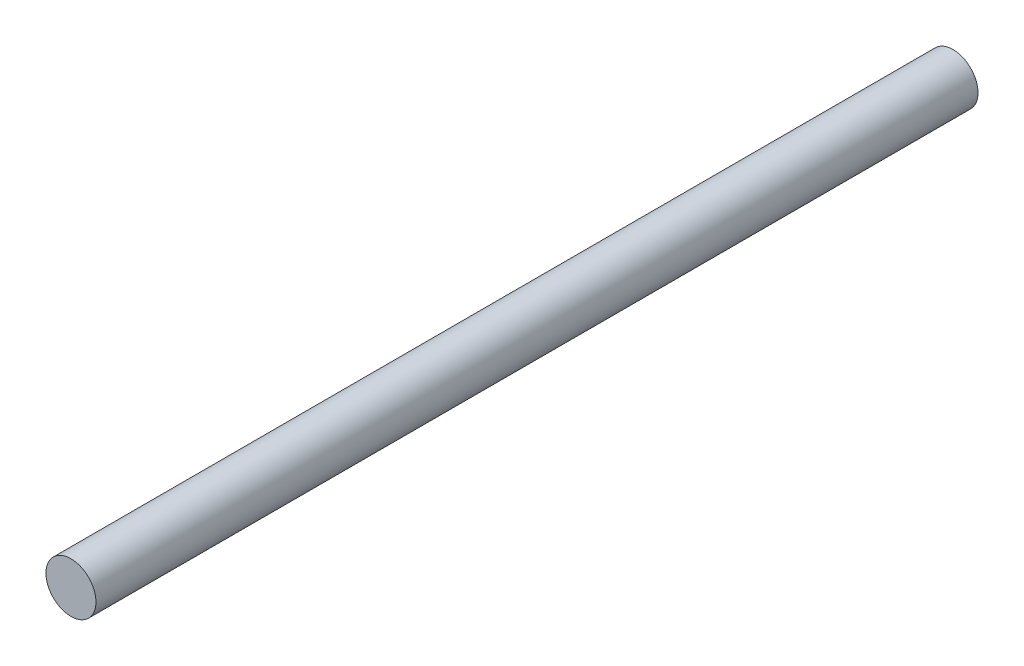
SolidWorks part; units mm, degrees
ref_plane "前视基准面" through (0, 0, 0) normal (0, 0, 1) x (1, 0, 0)
ref_plane "上视基准面" through (0, 0, 0) normal (0, 1, 0) x (1, 0, 0)
ref_plane "右视基准面" through (0, 0, 0) normal (1, 0, 0) x (0, 0, -1)
other "Configuration Table"
sketch "草图1" plane through (0, 0, 0) normal (0, 0, 1) x (1, 0, 0)
  circle A0 centre (0, 0) radius 2.5
  dimension "D1" = 5
extrude "凸台-拉伸1" add sketch "草图1" along normal blind 88.2
cosmetic thread "装饰螺纹线1" parameters "D1"=6.6, "D2"=4
cosmetic thread "装饰螺纹线3" parameters "D1"=5, "D2"=4
ref_plane "基准面1" through (0, 0, 73.2) normal (0, 0, 1) x (1, 0, 0)
sketch "草图2" plane through (0, 0, 73.2) normal (0, 0, 1) x (1, 0, 0)
  circle A0 centre (0, 0) radius 12.5
  dimension "D1" = 25
extrude "凸台-拉伸2" add sketch "草图2" against normal blind 62
ref_plane "基准面2" through (0, 0, 73.2) normal (0, 0, 1) x (1, 0, 0)
sketch "草图3" plane through (0, 0, 73.2) normal (0, 0, 1) x (1, 0, 0)
  line L4 (0, 8.8652) -> (0, -8.8652)
  line L5 (0, -8.8652) -> (40, -8.8652)
  line L6 (40, -8.8652) -> (40, 8.8652)
  line L7 (40, 8.8652) -> (0, 8.8652)
  line L8 (-12.5, 0) -> (19.0607, 0) construction
  circle A1 centre (0, 0) radius 12.5 construction
  circle A2 centre (32.64, 0) radius 5
  dimension "D2" = 10
  dimension "D1" = 40
extrude "凸台-拉伸3" add sketch "草图3" against normal blind 3
cosmetic thread "装饰螺纹线2" parameters "D2"=11
pattern_linear "阵列(线性)1" count 2 spacing 59 along (0, 0, -1) of "凸台-拉伸3"
sketch "草图4" plane through (0, 0, 73.2) normal (0, 0, 1) x (1, 0, 0)
  line L0 (0, 0) -> (0, 12.3344)
  line L1 (32.64, 0) -> (32.64, 15.3929)
sketch "草图5" plane through (0, 0, 88.2) normal (0, 0, 1) x (1, 0, 0)
  line L1 (8.8124, 8.8652) -> (40, 8.8652)
  line L3 (8.8124, -8.8652) -> (40, -8.8652)
  line L4 (40, 8.8652) -> (40, -8.8652)
  circle A0 centre (0, 0) radius 2.5
  arc A1 (8.8124, 8.8652) -> (8.8124, -8.8652) centre (0, 0) ccw
extrude "切除-拉伸1" cut sketch "草图5" against normal through all
